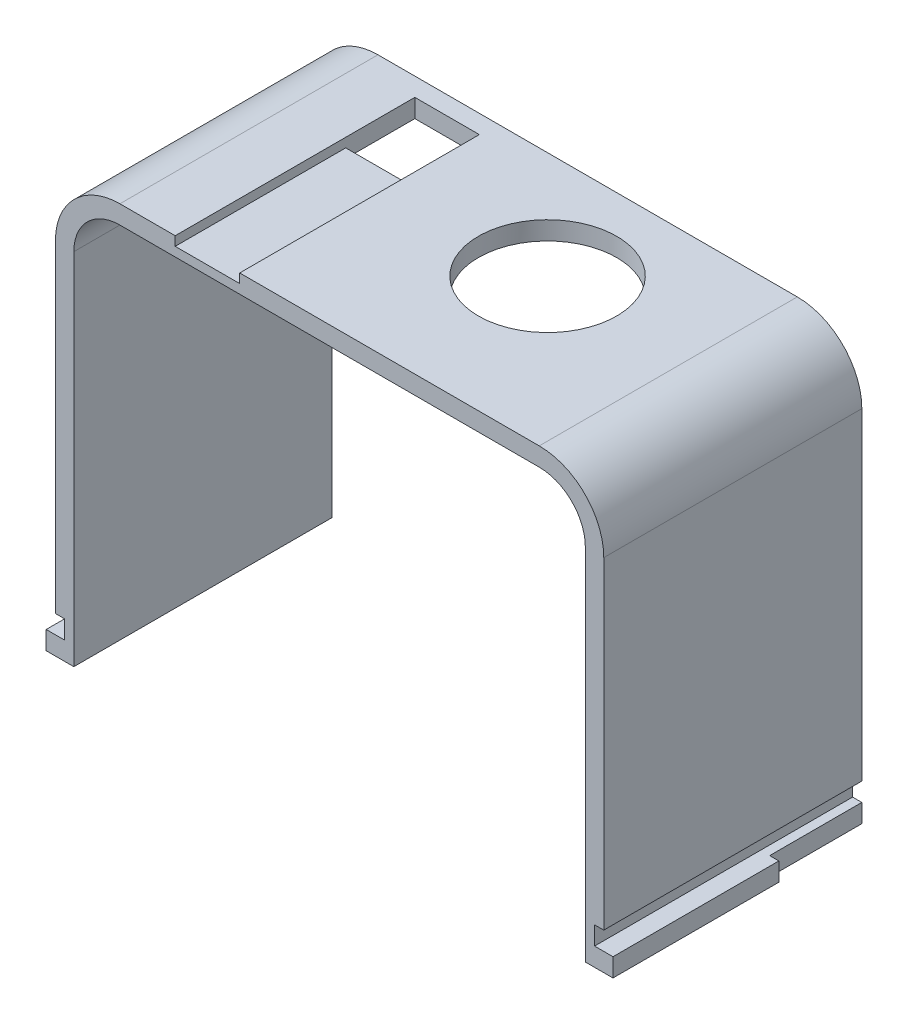
SolidWorks part; units mm, degrees
ref_plane "Front Plane" through (0, 0, 0) normal (0, 0, 1) x (1, 0, 0)
ref_plane "Top Plane" through (0, 0, 0) normal (0, 1, 0) x (1, 0, 0)
ref_plane "Right Plane" through (0, 0, 0) normal (1, 0, 0) x (0, 0, -1)
sketch "Sketch1" plane through (0, 0, 0) normal (0, 0, 1) x (1, 0, 0)
  line L0 (-30.589, 0) -> (-30.589, 33)
  line L1 (-25.589, 38) -> (19.911, 38)
  line L2 (24.911, 33) -> (24.911, 0)
  line L4 (26.911, 0) -> (26.911, 33)
  line L5 (19.911, 40) -> (-25.589, 40)
  line L6 (-32.589, 33) -> (-32.589, 0)
  line L8 (-2.839, 38) -> (-2.839, 40) construction
  line L11 (-32.589, 0) -> (-32.589, -6)
  line L12 (-32.589, -6) -> (-30.589, -6)
  line L13 (-30.589, 0) -> (-30.589, -6)
  line L15 (24.911, 0) -> (24.911, -6)
  line L16 (24.911, -6) -> (26.911, -6)
  line L17 (26.911, 0) -> (26.911, -6)
  arc A0 (19.911, 38) -> (24.911, 33) centre (19.911, 33) cw
  arc A1 (-30.589, 33) -> (-25.589, 38) centre (-25.589, 33) cw
  arc A2 (26.911, 33) -> (19.911, 40) centre (19.911, 33) ccw
  arc A3 (-25.589, 40) -> (-32.589, 33) centre (-25.589, 33) ccw
  point P19 (-32.589, 40)
  dimension "D4" = 5
  dimension "D5" = 7
  dimension "D1" = 40
  dimension "D2" = 2
  dimension "D3" = 2
  dimension "D6" = 59.5
  dimension "D7" = 6
extrude "Boss-Extrude1" add sketch "Sketch1" along normal blind 28
sketch "Sketch2" plane through (0, 0, 28) normal (0, 0, 1) x (1, 0, 0)
  line L1 (-32.589, -6) -> (-33.589, -6)
  line L2 (-32.589, -6) -> (-32.589, -4)
  line L3 (-32.589, -4) -> (-33.589, -4)
  line L4 (-33.589, -6) -> (-33.589, -4)
  line L5 (26.911, -6) -> (27.911, -6)
  line L6 (26.911, -6) -> (26.911, -4)
  line L7 (26.911, -4) -> (27.911, -4)
  line L8 (27.911, -6) -> (27.911, -4)
  dimension "D1" = 1
  dimension "D2" = 2
extrude "Boss-Extrude2" add sketch "Sketch2" against normal through all
sketch "Sketch3" plane through (0, 0, 28) normal (0, 0, 1) x (1, 0, 0)
  line L1 (-32.589, -4) -> (-31.589, -4)
  line L2 (-32.589, -4) -> (-32.589, -2)
  line L3 (-32.589, -2) -> (-31.589, -2)
  line L4 (-31.589, -4) -> (-31.589, -2)
  line L5 (26.911, -4) -> (25.911, -4)
  line L6 (26.911, -4) -> (26.911, -2)
  line L7 (26.911, -2) -> (25.911, -2)
  line L8 (25.911, -4) -> (25.911, -2)
  dimension "D1" = 1
  dimension "D2" = 2
extrude "Cut-Extrude1" cut sketch "Sketch3" against normal through all
sketch "Sketch4" plane through (0, 40, 0) normal (0, 1, 0) x (1, 0, 0)
  line L0 (4.411, -11.6) -> (4.411, 0) construction
  line L1 (19.911, 0) -> (-25.589, 0) construction
  line L2 (4.411, -11.6) -> (19.911, -11.6) construction
  line L3 (19.911, -28) -> (19.911, 0) construction
  circle A0 centre (4.411, -11.6) radius 7.5
  dimension "D3" = 15
  dimension "D1" = 15.5
  dimension "D2" = 11.6
extrude "Cut-Extrude2" cut sketch "Sketch4" against normal blind 10
sketch "Sketch5" plane through (0, 0, 0) normal (0, 0, -1) x (-1, 0, 0)
  line L0 (-27.911, -4) -> (-25.911, -4) construction
  line L1 (-26.911, -4) -> (-27.911, -4)
  line L2 (-26.911, -4) -> (-26.911, -6)
  line L3 (-26.911, -6) -> (-27.911, -6)
  line L4 (-27.911, -4) -> (-27.911, -6)
extrude "Cut-Extrude3" cut sketch "Sketch5" against normal blind 10
sketch "Sketch6" plane through (0, 40, 0) normal (0, 1, 0) x (1, 0, 0)
  line L0 (-19.589, -2) -> (-25.589, -2) construction
  line L1 (-19.589, -9.5) -> (-12.589, -9.5)
  line L2 (-19.589, -9.5) -> (-19.589, -2)
  line L3 (-19.589, -2) -> (-12.589, -2)
  line L4 (-12.589, -9.5) -> (-12.589, -2)
  line L5 (-25.589, -28) -> (-25.589, 0) construction
  line L6 (-19.589, -2) -> (-19.589, 0) construction
  line L7 (19.911, 0) -> (-25.589, 0) construction
  dimension "D1" = 7.5
  dimension "D2" = 7
  dimension "D3" = 6
  dimension "D4" = 2
extrude "Cut-Extrude4" cut sketch "Sketch6" against normal blind 2
sketch "Sketch7" plane through (0, 40, 0) normal (0, 1, 0) x (1, 0, 0)
  line L0 (19.911, -28) -> (-25.589, -28) construction
  line L1 (-19.589, -9.5) -> (-12.589, -9.5)
  line L2 (-19.589, -9.5) -> (-19.589, -28)
  line L3 (-19.589, -28) -> (-12.589, -28)
  line L4 (-12.589, -9.5) -> (-12.589, -28)
extrude "Cut-Extrude5" cut sketch "Sketch7" against normal blind 1
